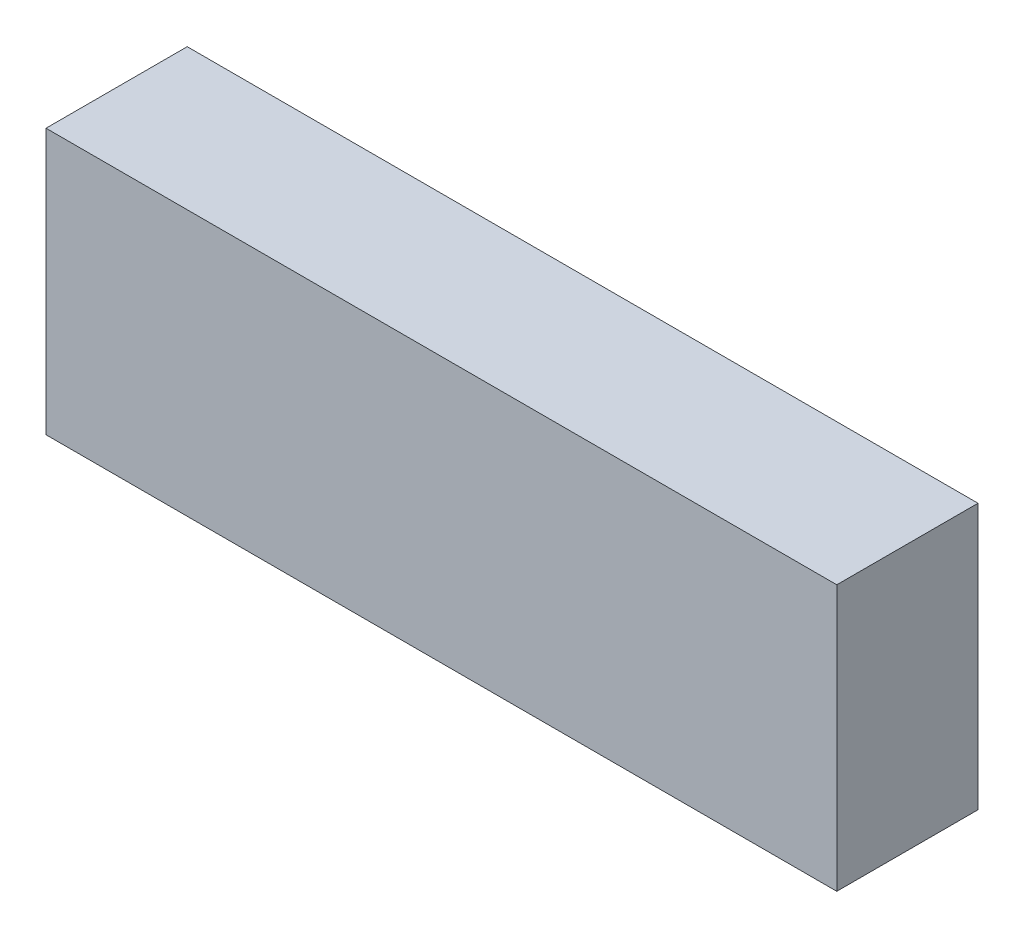
SolidWorks part; units mm, degrees
ref_plane "Alzado" through (0, 0, 0) normal (0, 0, 1) x (1, 0, 0)
ref_plane "Planta" through (0, 0, 0) normal (0, 1, 0) x (1, 0, 0)
ref_plane "Vista lateral" through (0, 0, 0) normal (1, 0, 0) x (0, 0, -1)
sketch "Croquis1" plane through (0, 0, 0) normal (0, 0, 1) x (1, 0, 0)
  line L1 (-70, 23.5) -> (70, 23.5)
  line L2 (-70, 23.5) -> (-70, -23.5)
  line L3 (-70, -23.5) -> (70, -23.5)
  line L4 (70, 23.5) -> (70, -23.5)
  line L5 (-70, 23.5) -> (70, -23.5) construction
  line L6 (-70, -23.5) -> (70, 23.5) construction
  point P0 (0, 0)
  dimension "D1" = 140
  dimension "D2" = 47
extrude "Saliente-Extruir1" add sketch "Croquis1" along normal blind 25
equation "\"Largo\" = 140mm"
equation "\"Ancho\"= 47mm"
equation "\"Alto\"= 25mm"
